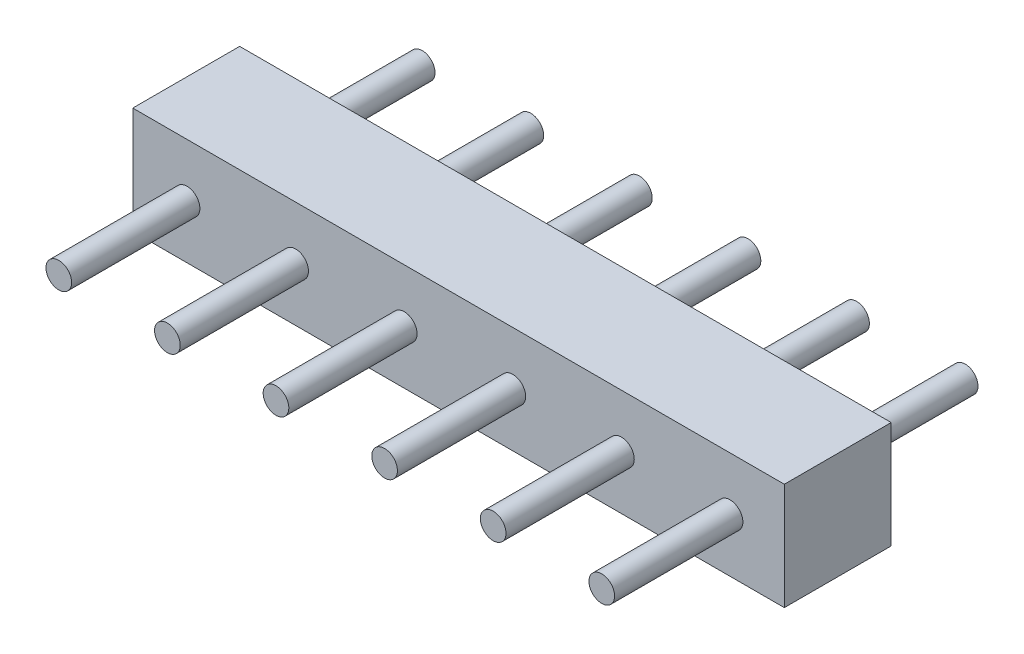
SolidWorks part; units mm, degrees
ref_plane "前视基准面" through (0, 0, 0) normal (0, 0, 1) x (1, 0, 0)
ref_plane "上视基准面" through (0, 0, 0) normal (0, 1, 0) x (1, 0, 0)
ref_plane "右视基准面" through (0, 0, 0) normal (1, 0, 0) x (0, 0, -1)
sketch "草图1" plane through (0, 0, 0) normal (0, 0, 1) x (1, 0, 0)
  line L1 (0, 0) -> (15.24, 0)
  line L2 (0, 0) -> (0, 2.5)
  line L3 (0, 2.5) -> (15.24, 2.5)
  line L4 (15.24, 0) -> (15.24, 2.5)
  dimension "D1" = 2.5
  dimension "D2" = 15.24
extrude "凸台-拉伸1" add sketch "草图1" along normal blind 2.5
sketch "草图2" plane through (0, 0, 2.5) normal (0, 0, 1) x (1, 0, 0)
  line L0 (7.62, 2.5) -> (7.62, -1.7995) construction
  line L1 (15.24, 2.5) -> (0, 2.5) construction
  line L2 (0, 1.25) -> (15.9024, 1.25) construction
  line L3 (0, 2.5) -> (0, 0) construction
  circle A0 centre (6.35, 1.25) radius 0.3
  dimension "D1" = 1.27
  dimension "D2" = 0.6
extrude "凸台-拉伸2" add sketch "草图2" along normal blind 3 and the other way blind 5.5
pattern_linear "阵列(线性)1" count 4 spacing 2.54 along (1, 0, 0) count 3 spacing 2.54 along (-1, 0, 0) of "凸台-拉伸2"
